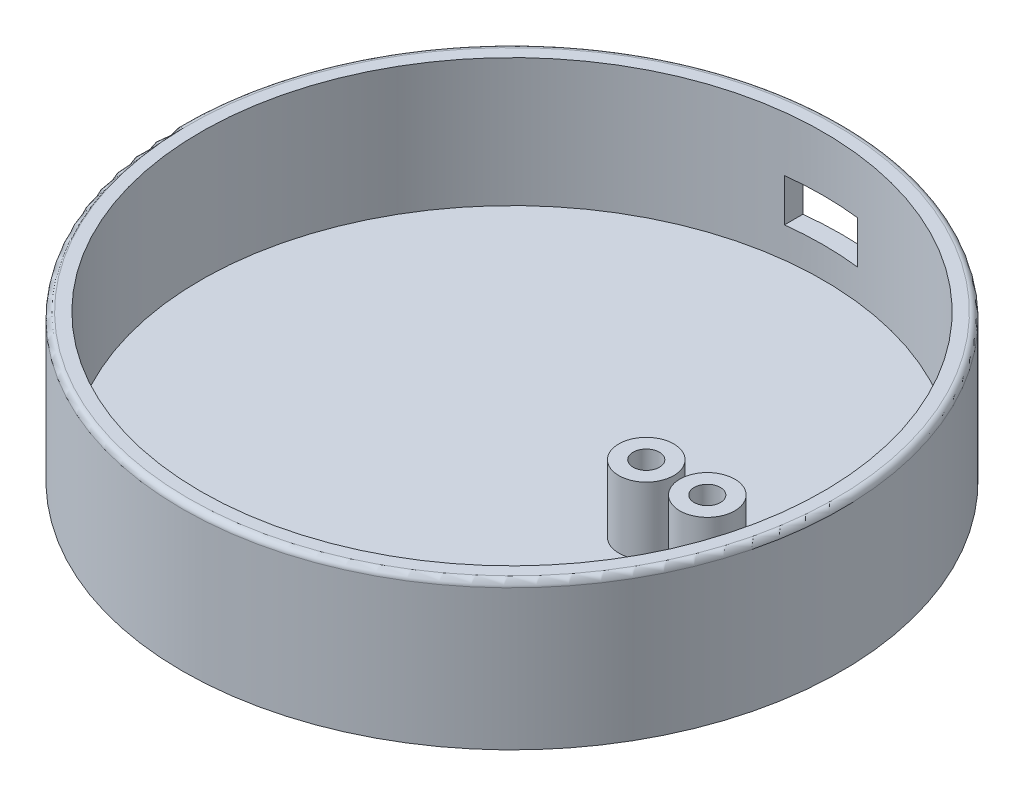
SolidWorks part; units mm, degrees
ref_plane "前视基准面" through (0, 0, 0) normal (0, 0, 1) x (1, 0, 0)
ref_plane "上视基准面" through (0, 0, 0) normal (0, 1, 0) x (1, 0, 0)
ref_plane "右视基准面" through (0, 0, 0) normal (1, 0, 0) x (0, 0, -1)
other "Configuration Table"
sketch "草图1" plane through (0, 0, 0) normal (0, 1, 0) x (1, 0, 0)
  circle A0 centre (0, 0) radius 54
extrude "Floor_D108_T3" add sketch "草图1" along normal blind 3
sketch "草图2" plane through (0, 0, 0) normal (0, 1, 0) x (1, 0, 0)
  circle A0 centre (0, 0) radius 54
  circle A1 centre (0, 0) radius 51
extrude "Rim_OD108_ID102_H24" add sketch "草图2" along normal blind 24
sketch "草图3" plane through (0, 0, 0) normal (0, 1, 0) x (1, 0, 0)
  circle A0 centre (22, 0) radius 4.5
  circle A1 centre (32, 0) radius 4.5
extrude "Sensor_fixed_posts" add sketch "草图3" along normal blind 14
sketch "草图4" plane through (0, 0, 0) normal (0, 1, 0) x (1, 0, 0)
  circle A0 centre (22, 0) radius 2.15
  circle A1 centre (32, 0) radius 2.15
extrude "M4_fixed_mount_clearance" cut sketch "草图4" along normal blind 14
ref_plane "基准面1" through (0, 8, 0) normal (0, 1, 0) x (1, 0, 0)
sketch "草图5" plane through (0, 8, 0) normal (0, 1, 0) x (1, 0, 0)
  line L1 (-6, 49) -> (6, 49)
  line L2 (-6, 49) -> (-6, 60)
  line L3 (-6, 60) -> (6, 60)
  line L4 (6, 49) -> (6, 60)
extrude "USB_C_side_opening_12x7" cut sketch "草图5" along normal blind 7
fillet "Base_outer_round_R1" radius 1 1 edges at (0, 24, 54)
